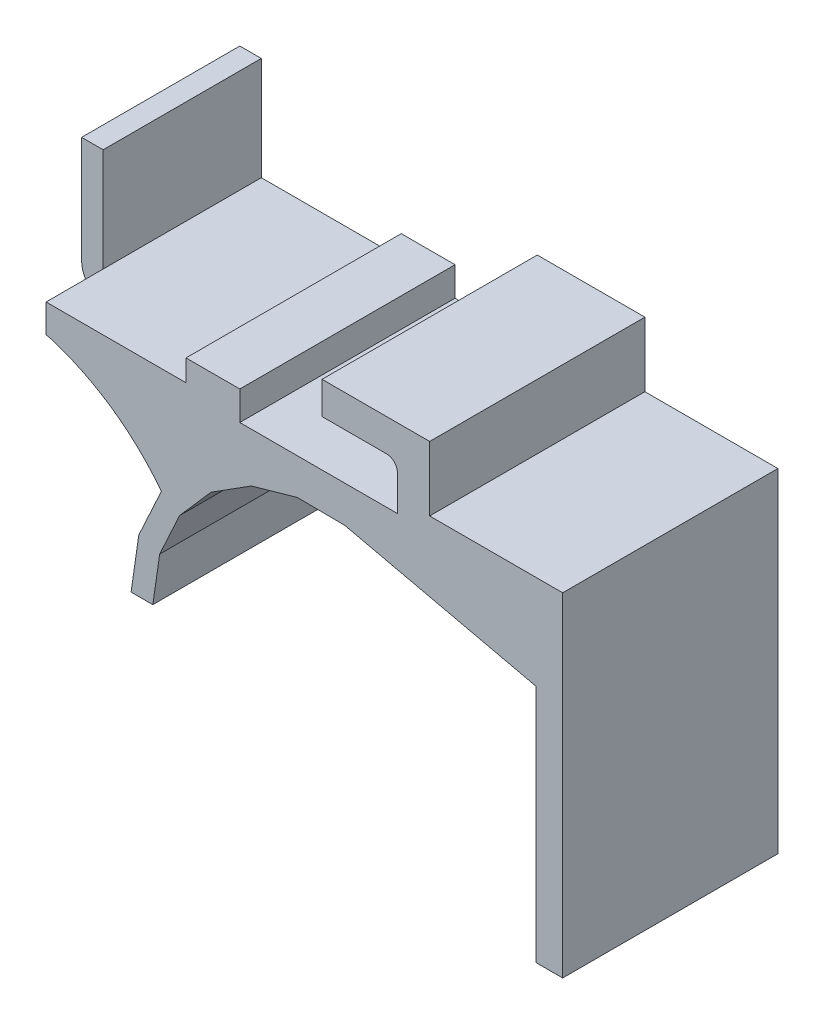
SolidWorks part; units mm, degrees
ref_plane "Alzado" through (0, 0, 0) normal (0, 0, 1) x (1, 0, 0)
ref_plane "Planta" through (0, 0, 0) normal (0, 1, 0) x (1, 0, 0)
ref_plane "Vista lateral" through (0, 0, 0) normal (1, 0, 0) x (0, 0, -1)
sketch "Croquis2" plane through (0, 0, 0) normal (0, 0, 1) x (1, 0, 0)
  line L0 (-51.9511, -1.694) -> (-49.9511, -1.694)
  line L1 (-49.9511, -1.694) -> (-51.9511, -1.694)
  line L2 (-1.9511, -10.694) -> (-1.9511, -41.694)
  line L3 (-1.9511, -41.694) -> (-51.9511, -41.694) construction
  line L4 (-51.9511, -1.694) -> (-51.9511, -41.694) construction
  line L5 (-49.9511, -1.694) -> (-49.9511, -11.294)
  line L6 (-49.9511, -11.294) -> (-36.9511, -11.294)
  line L7 (-36.9511, -11.294) -> (-36.9511, -9.294)
  line L8 (-36.9511, -9.294) -> (-31.9511, -9.294)
  line L9 (-31.9511, -9.294) -> (-31.9511, -11.994)
  line L10 (-31.9511, -11.994) -> (-17.3111, -11.994)
  line L11 (-17.3111, -11.994) -> (-17.3111, -7.694)
  line L12 (-17.3111, -7.694) -> (-24.3111, -7.694)
  line L13 (-24.3111, -7.694) -> (-24.3111, -4.694)
  line L14 (-24.3111, -4.694) -> (-14.3111, -4.694)
  line L15 (-14.3111, -4.694) -> (-14.3111, -10.694)
  line L16 (-14.3111, -10.694) -> (-1.9511, -10.694)
  line L17 (-1.9511, -41.694) -> (-4.5642, -41.694)
  line L18 (-4.5642, -41.694) -> (-4.5642, -19.454)
  line L19 (-4.5642, -19.454) -> (-22.3242, -19.454) construction
  line L20 (-22.3242, -41.694) -> (-22.3242, -15.394) construction
  line L21 (-4.5642, -19.454) -> (-22.3242, -15.394)
  line L22 (-42.1842, -30.694) -> (-40.1642, -30.694)
  line L23 (-22.3242, -15.394) -> (-26.7442, -15.394) construction
  line L24 (-42.1842, -41.694) -> (-42.1842, -30.694) construction
  line L25 (-40.1642, -41.694) -> (-40.1642, -30.694) construction
  line L26 (-26.7442, -15.394) -> (-26.7442, -15.354)
  line L27 (-22.3242, -15.394) -> (-26.7442, -15.354)
  line L28 (-40.1642, -30.694) -> (-26.7442, -15.354) construction
  arc A0 (-40.1642, -30.694) -> (-26.7442, -15.354) centre (-26.4173, -29.1801) cw
  dimension "D1" = 2
  dimension "D2" = 50
  dimension "D3" = 40
  dimension "D4" = 9.6
  dimension "D5" = 13
  dimension "D6" = 2
  dimension "D7" = 5
  dimension "D8" = 2.7
  dimension "D9" = 14.64
  dimension "D10" = 4.3
  dimension "D11" = 3
  dimension "D12" = 10
  dimension "D13" = 6
  dimension "D14" = 12.36
  dimension "D15" = 22.24
  dimension "D16" = 17.76
  dimension "D17" = 26.3
  dimension "D18" = 35.6
  dimension "D19" = 2.02
  dimension "D20" = 11
  dimension "D21" = 4.42
  dimension "D22" = 0.04
sketch "Croquis3" plane through (0, 0, 0) normal (0, 0, 1) x (1, 0, 0)
  line L0 (-51.9527, -11.691) -> (-51.8744, -12.2863)
  line L1 (-51.8744, -12.2863) -> (-51.6446, -12.841)
  line L2 (-51.6446, -12.841) -> (-51.2791, -13.3174)
  line L3 (-51.2791, -13.3174) -> (-50.8027, -13.6829)
  line L4 (-50.248, -13.9127) -> (-49.6525, -13.9915)
  line L5 (-50.8027, -13.6829) -> (-50.248, -13.9127)
  line L6 (-49.6525, -13.9915) -> (-48.6343, -14.3253)
  line L7 (-48.6343, -14.3253) -> (-47.6349, -14.7118)
  line L8 (-47.6349, -14.7118) -> (-46.6571, -15.1501)
  line L9 (-46.6571, -15.1501) -> (-45.7035, -15.6388)
  line L10 (-45.7035, -15.6388) -> (-44.7768, -16.1766)
  line L11 (-44.7768, -16.1766) -> (-43.8794, -16.7622)
  line L12 (-43.8794, -16.7622) -> (-43.0138, -17.3938)
  line L13 (-43.0138, -17.3938) -> (-42.1824, -18.0698)
  line L14 (-42.1824, -18.0698) -> (-41.3875, -18.7883)
  line L15 (-40.6312, -19.5474) -> (-39.9156, -20.3449)
  line L16 (-41.3875, -18.7883) -> (-40.6312, -19.5474)
  line L17 (-39.2426, -21.1787) -> (-39.9156, -20.3449)
  line L18 (-41.3372, -25.7329) -> (-39.2426, -21.1787)
  line L19 (-42.055, -30.694) -> (-41.3372, -25.7329)
  line L20 (-40.0342, -30.694) -> (-42.055, -30.694)
  line L21 (-40.0342, -30.694) -> (-39.3992, -26.3057)
  line L22 (-37.5465, -22.2773) -> (-39.3992, -26.3057)
  line L23 (-34.6279, -18.9394) -> (-37.5465, -22.2773)
  line L24 (-30.8828, -16.5656) -> (-34.6279, -18.9394)
  line L25 (-26.8105, -15.4054) -> (-30.8828, -16.5656)
  line L26 (-22.1958, -15.3943) -> (-26.6185, -15.3507)
  line L27 (-4.4311, -19.4548) -> (-22.1958, -15.3943)
  line L28 (-4.4311, -41.694) -> (-4.4311, -19.4548)
  line L29 (-1.9511, -41.694) -> (-4.4311, -41.694)
  line L30 (-1.9511, -41.694) -> (-1.9511, -10.694)
  line L31 (-14.3115, -10.694) -> (-1.9511, -10.694)
  line L32 (-14.3115, -10.694) -> (-14.3115, -4.694)
  line L33 (-24.3115, -4.694) -> (-14.3115, -4.694)
  line L34 (-24.3115, -7.694) -> (-24.3115, -4.694)
  line L35 (-18.3115, -7.694) -> (-24.3115, -7.694)
  line L36 (-17.3115, -11.994) -> (-17.3115, -8.694)
  line L37 (-17.3115, -11.994) -> (-31.9525, -11.994)
  line L38 (-31.9525, -9.294) -> (-31.9525, -11.994)
  line L39 (-31.9525, -9.294) -> (-36.9525, -9.294)
  line L40 (-36.9525, -9.294) -> (-36.9525, -11.294)
  line L41 (-36.9525, -11.294) -> (-49.9525, -11.294)
  line L42 (-49.9525, -1.694) -> (-49.9525, -11.294)
  line L43 (-51.9515, -1.6938) -> (-49.9525, -1.694)
  line L44 (-51.9515, -1.6938) -> (-51.9527, -11.691)
  line L52 (-17.3115, -8.694) -> (-17.3455, -8.4351)
  line L54 (-17.4454, -8.194) -> (-17.3455, -8.4351)
  line L55 (-17.6044, -7.9869) -> (-17.4454, -8.194)
  line L56 (-17.8115, -7.8279) -> (-17.6044, -7.9869)
  line L57 (-18.0527, -7.728) -> (-17.8115, -7.8279)
  line L58 (-18.3115, -7.694) -> (-18.0527, -7.728)
  line L59 (-26.6185, -15.3507) -> (-26.8105, -15.4054)
  arc A4 (-18.3115, -7.694) -> (-17.3115, -8.694) centre (-18.3115, -8.694) cw
  dimension "D1" = 2.48
extrude "Saliente-Extruir1" add sketch "Croquis3" along normal blind 20 contours L35 A4 L36 L37 L38 L39 L40 L41 L42 L43 L44 L0 L1 L2 L3 L5 L4 L6 L7 L8 L9 L10 L11 L12 L13 L14 L16 L15 L17 L18 L19 L20 L21 L22 L23 L24 L25 L59 L26 L27 L28 L29 L30 L31 L32 L33
sketch "Croquis5" plane through (0, 0, 20) normal (0, 0, 1) x (1, 0, 0)
  line L0 (-49.9525, -11.294) -> (-49.9503, -13.9521)
  line L1 (-50.248, -13.9127) -> (-49.6525, -13.9915) construction
  line L2 (-49.9525, -11.294) -> (-49.9525, -1.694)
  line L3 (-49.9525, -1.694) -> (-51.9515, -1.6938)
  line L4 (-51.9515, -1.6938) -> (-51.9527, -11.691)
  line L5 (-51.9527, -11.691) -> (-51.8744, -12.2863) construction
  line L6 (-51.8744, -12.2863) -> (-51.6446, -12.841) construction
  line L7 (-51.6446, -12.841) -> (-51.2791, -13.3174) construction
  line L8 (-51.2791, -13.3174) -> (-50.8027, -13.6829) construction
  line L9 (-50.8027, -13.6829) -> (-50.248, -13.9127) construction
  line L30 (-51.9527, -11.691) -> (-51.8744, -12.2863)
  line L31 (-51.8744, -12.2863) -> (-51.6446, -12.841)
  line L32 (-51.6446, -12.841) -> (-51.2791, -13.3174)
  line L33 (-51.2791, -13.3174) -> (-50.8027, -13.6829)
  line L34 (-50.8027, -13.6829) -> (-50.248, -13.9127)
  line L35 (-50.248, -13.9127) -> (-49.9503, -13.9521)
extrude "Cortar-Extruir2" cut sketch "Croquis5" against normal blind 5.3
